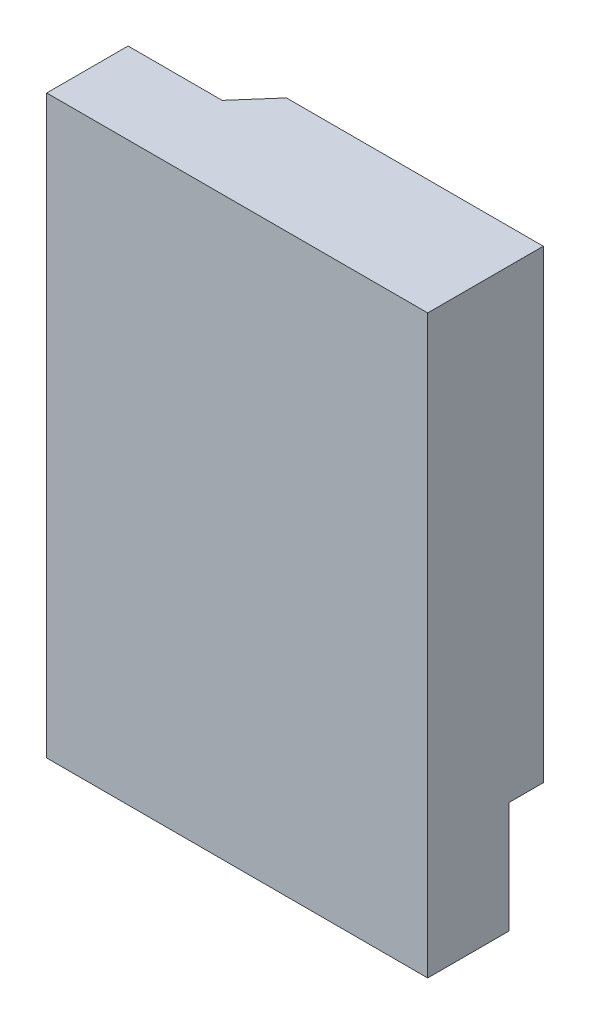
SolidWorks part; units mm, degrees
ref_plane "Front Plane" through (0, 0, 0) normal (0, 0, 1) x (1, 0, 0)
ref_plane "Top Plane" through (0, 0, 0) normal (0, 1, 0) x (1, 0, 0)
ref_plane "Right Plane" through (0, 0, 0) normal (1, 0, 0) x (0, 0, -1)
sketch "Sketch1" plane through (0, 0, 0) normal (0, 0, 1) x (1, 0, 0)
  line L1 (-22.25, -33.6371) -> (22.25, -33.6371)
  line L2 (-22.25, -33.6371) -> (-22.25, 33.6371)
  line L3 (-22.25, 33.6371) -> (22.25, 33.6371)
  line L4 (22.25, -33.6371) -> (22.25, 33.6371)
  line L5 (-22.25, -33.6371) -> (22.25, 33.6371) construction
  line L6 (-22.25, 33.6371) -> (22.25, -33.6371) construction
  point P0 (0, 0)
extrude "Boss-Extrude1" add sketch "Sketch1" along normal blind 13.5
sketch "Sketch2" plane through (0, 33.6371, 0) normal (0, 1, 0) x (1, 0, 0)
  line L0 (-22.25, 0) -> (-7.75, 0)
  line L1 (22.25, 0) -> (-22.25, 0) construction
  line L3 (-11.25, -4) -> (-7.75, 0)
  line L4 (-22.25, -13.5) -> (-22.25, 0) construction
  line L5 (-22.25, -4) -> (-22.25, 0)
  line L6 (-22.25, -4) -> (-11.25, -4)
extrude "Cut-Extrude1" cut sketch "Sketch2" against normal blind 73.5
sketch "Sketch3" plane through (0, -33.6371, 0) normal (0, -1, 0) x (1, 0, 0)
  line L0 (22.25, 13.5) -> (8.05, 13.5)
  line L1 (-22.25, 13.5) -> (22.25, 13.5) construction
  line L2 (22.25, 13.5) -> (22.25, 9.5)
  line L3 (22.25, 13.5) -> (22.25, 0) construction
  line L4 (22.25, 9.5) -> (12.5, 9.5)
  line L5 (12.5, 9.5) -> (8.05, 13.5)
extrude "Cut-Extrude2" cut sketch "Sketch3" against normal blind 14
sketch "Sketch6" plane through (0, -33.6371, 0) normal (0, -1, 0) x (-1, 0, 0)
  line L0 (-22.25, -9.5) -> (-12.5, -9.5)
  line L1 (-12.5, -9.5) -> (-8.05, -13.5)
  line L2 (-8.05, -13.5) -> (-22.25, -13.5)
  line L3 (-22.25, -13.5) -> (-22.25, -9.5)
extrude "Boss-Extrude2" add sketch "Sketch6" against normal up to surface (14 mm away) up to face at (16.2625, -19.6371, 11.5)
sketch "Sketch7" plane through (0, -33.6371, 0) normal (0, -1, 0) x (1, 0, 0)
  line L0 (22.25, 0) -> (8.05, 0)
  line L1 (-7.75, 0) -> (22.25, 0) construction
  line L2 (22.25, 0) -> (22.25, 4)
  line L3 (22.25, 13.5) -> (22.25, 0) construction
  line L4 (22.25, 4) -> (13.25, 4)
  line L5 (13.25, 4) -> (8.05, 0)
extrude "Cut-Extrude6" cut sketch "Sketch7" against normal blind 13
sketch "Sketch9" plane through (0, 0, 0) normal (0, 0, -1) x (-1, 0, 0)
  text T0 "<b>A</b>\r\n<b>R</b>\r\n<b>D</b>\r\n<b>U</b>\r\n<b>C</b>\r\n<b>O</b>\r\n<b>P</b>\r\n<b>T</b>\r\n<b>E</b>\r\n<b>R</b>"
extrude "Cut-Extrude8" cut sketch "Sketch9" against normal blind 2
